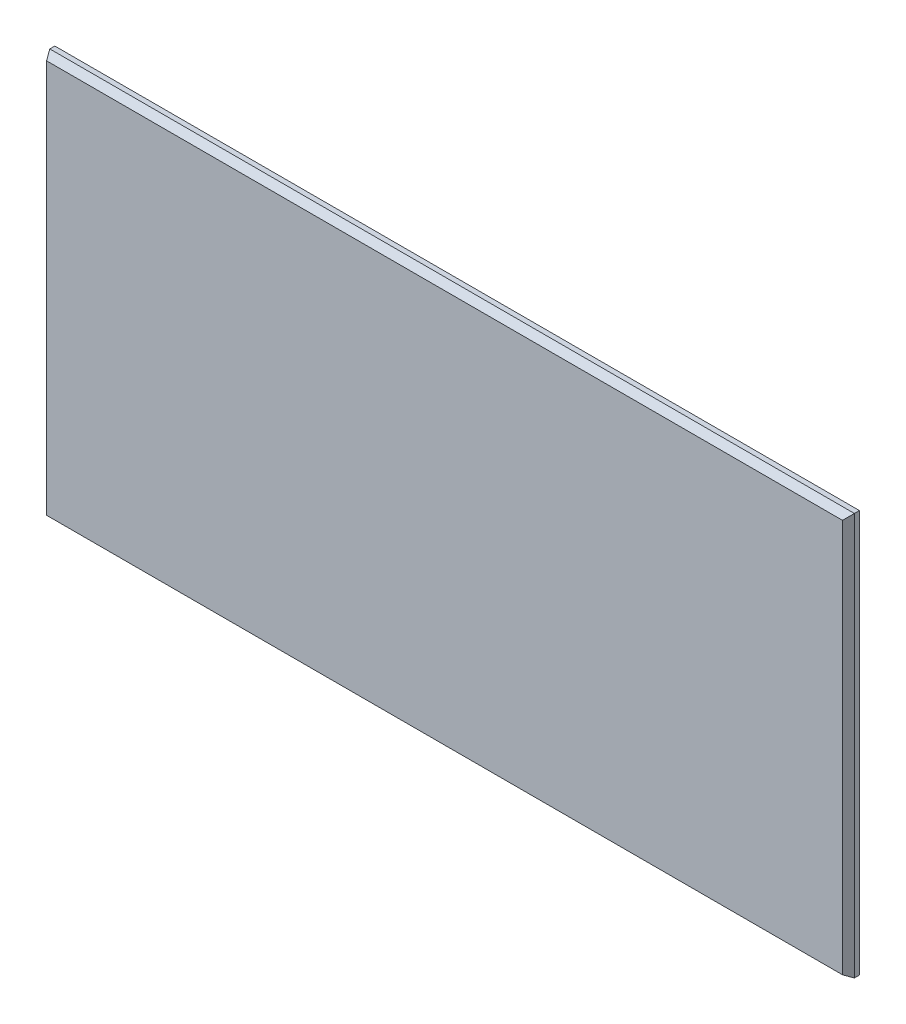
SolidWorks part; units mm, degrees
ref_plane "Front Plane" through (0, 0, 0) normal (0, 0, 1) x (1, 0, 0)
ref_plane "Top Plane" through (0, 0, 0) normal (0, 1, 0) x (1, 0, 0)
ref_plane "Right Plane" through (0, 0, 0) normal (1, 0, 0) x (0, 0, -1)
sketch "Sketch1" plane through (0, 0, 0) normal (0, 0, 1) x (1, 0, 0)
  line L0 (0, 25.4) -> (0, -25.4)
  line L1 (-50.8, 0) -> (50.8, 0)
  point P4 (0, 0)
  point P8 (0, 0)
  dimension "Width" = 101.6
  dimension "Height" = 50.8
sketch "Sketch2" plane through (0, 0, 0) normal (1, 0, 0) x (0, 0, -1)
  line L0 (-0.7937, 0) -> (0.7937, 0)
  point P3 (0, 0)
  dimension "Thickness" = 1.5875
ref_plane "Plane1" through (0, 0, -0.7937) normal (0, 0, 1) x (1, 0, 0)
sketch "Sketch3" plane through (0, 0, -0.7937) normal (0, 0, 1) x (1, 0, 0)
  line L1 (-50.8, 25.4) -> (50.8, 25.4)
  line L2 (-50.8, 25.4) -> (-50.8, -25.4)
  line L3 (-50.8, -25.4) -> (50.8, -25.4)
  line L4 (50.8, 25.4) -> (50.8, -25.4)
extrude "Boss-Extrude1" add sketch "Sketch3" along normal blind 0.635
sketch "Sketch4" plane through (0, 0, -0.1587) normal (0, 0, 1) x (1, 0, 0)
  line L4 (-50.8, 25.4) -> (-50.8, -25.4)
  line L5 (-50.8, -25.4) -> (50.8, -25.4)
  line L6 (50.8, -25.4) -> (50.8, 25.4)
  line L7 (50.8, 25.4) -> (-50.8, 25.4)
  line L8 (-50.8, 25.4) -> (-50.8, -25.4)
  line L9 (-50.8, -25.4) -> (50.8, -25.4)
  line L10 (50.8, -25.4) -> (50.8, 25.4)
  line L11 (50.8, 25.4) -> (-50.8, 25.4)
  dimension "D1" = 0
extrude "Boss-Extrude2" add sketch "Sketch4" along normal up to vertex (0.9525 mm away) draft 30 up to point (0, 0, 0.7937)
equation "\"D1@Boss-Extrude1\"=\"Thickness@Sketch2\"/2.5"
